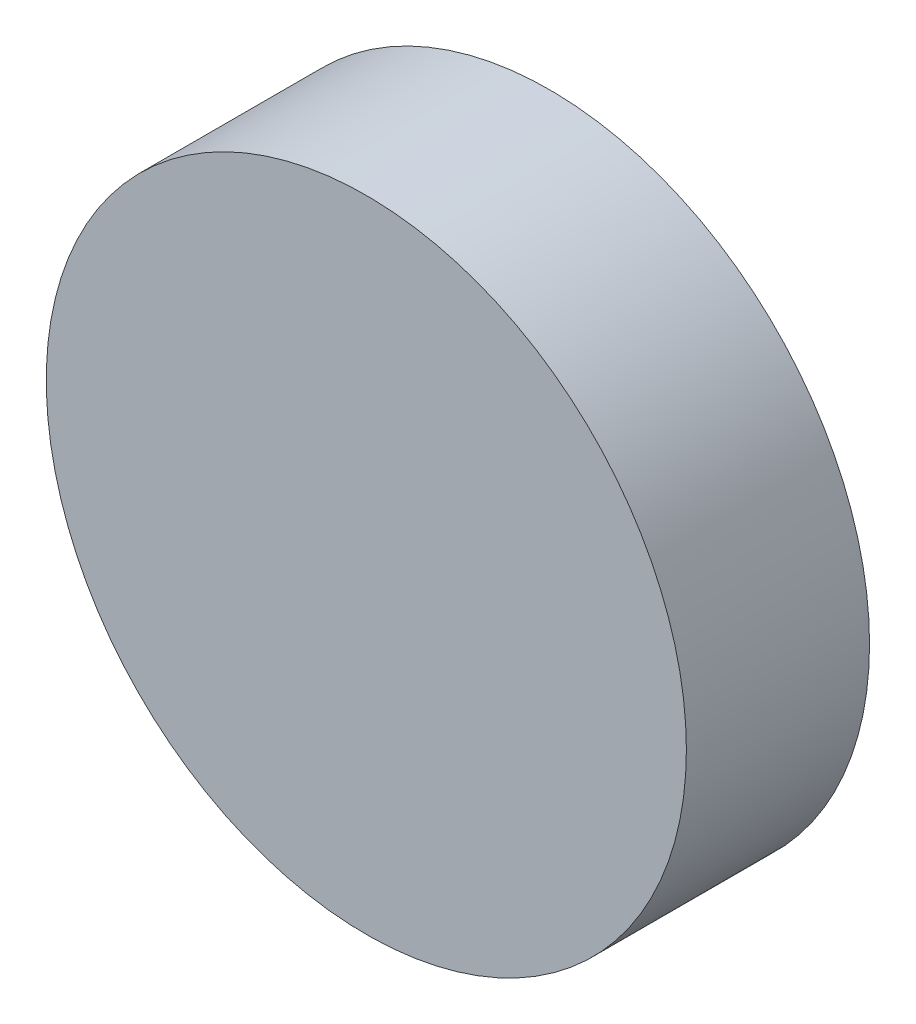
SolidWorks part; units mm, degrees
ref_plane "Front Plane" through (0, 0, 0) normal (0, 0, 1) x (1, 0, 0)
ref_plane "Top Plane" through (0, 0, 0) normal (0, 1, 0) x (1, 0, 0)
ref_plane "Right Plane" through (0, 0, 0) normal (1, 0, 0) x (0, 0, -1)
other "Configuration Table"
sketch "Sketch1" plane through (0, 0, 0) normal (0, 0, 1) x (1, 0, 0)
  circle A0 centre (0, 0) radius 10.7145
extrude "Boss-Extrude1" add sketch "Sketch1" along normal blind 6.1314
